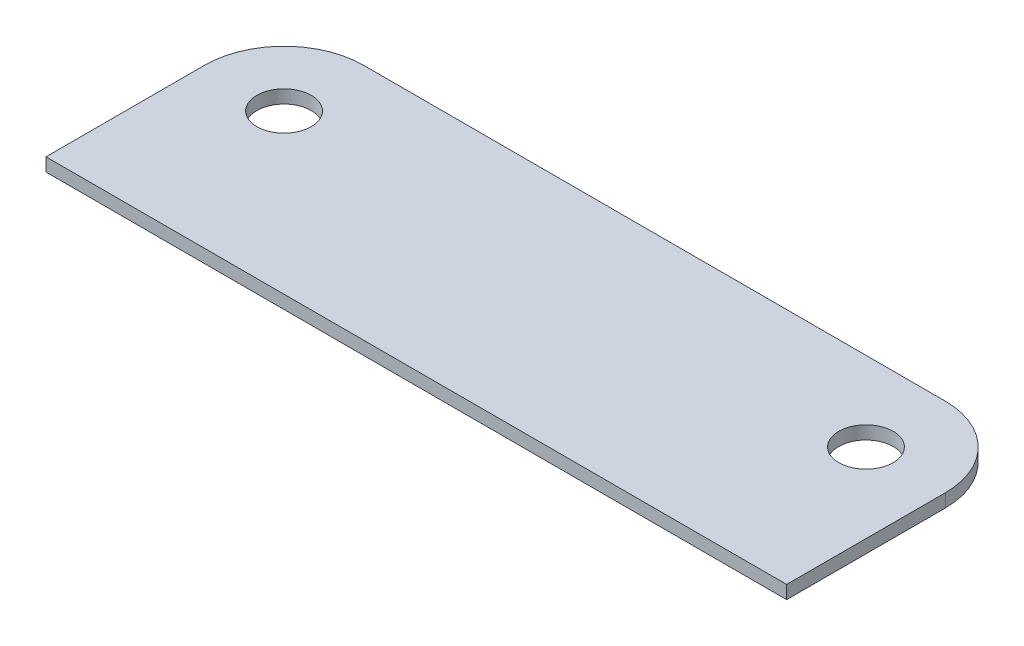
SolidWorks part; units mm, degrees
material "AISI 1020"
ref_plane "Front Plane" through (0, 0, 0) normal (0, 0, 1) x (1, 0, 0)
ref_plane "Top Plane" through (0, 0, 0) normal (0, 1, 0) x (1, 0, 0)
ref_plane "Right Plane" through (0, 0, 0) normal (1, 0, 0) x (0, 0, -1)
sketch "Sketch1" plane through (0, 0, 0) normal (0, 1, 0) x (1, 0, 0)
  line L0 (-44.45, 0) -> (44.45, 0)
  line L1 (44.45, 0) -> (44.45, 19.05)
  line L3 (-44.45, 19.05) -> (-44.45, 0)
  line L5 (-34.925, 28.575) -> (34.925, 28.575)
  arc A0 (44.45, 19.05) -> (34.925, 28.575) centre (34.925, 19.05) ccw
  arc A1 (-34.925, 28.575) -> (-44.45, 19.05) centre (-34.925, 19.05) ccw
  circle A2 centre (-34.925, 19.05) radius 3.2639
  circle A3 centre (34.925, 19.05) radius 3.2639
  point P4 (0, 0)
  dimension "D1" = 88.9
  dimension "D2" = 6.5278
  dimension "D3" = 19.05
  dimension "D4" = 69.85
extrude "Boss-Extrude1" add sketch "Sketch1" along normal blind 1.5875
